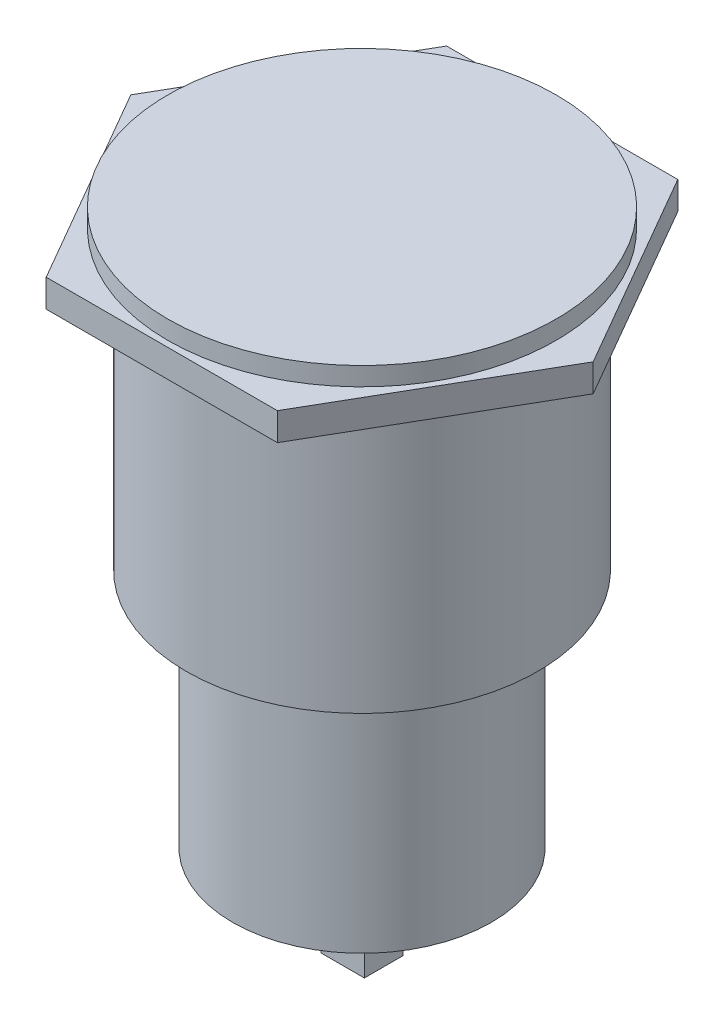
SolidWorks part; units mm, degrees
ref_plane "Front Plane" through (0, 0, 0) normal (0, 0, 1) x (1, 0, 0)
ref_plane "Top Plane" through (0, 0, 0) normal (0, 1, 0) x (1, 0, 0)
ref_plane "Right Plane" through (0, 0, 0) normal (1, 0, 0) x (0, 0, -1)
sketch "Sketch1" plane through (0, 0, 0) normal (0, 1, 0) x (1, 0, 0)
  circle A0 centre (0, 0) radius 9.5
  dimension "D1" = 19
extrude "Boss-Extrude1" add sketch "Sketch1" against normal blind 14.5
sketch "Sketch2" plane through (0, -14.5, 0) normal (0, -1, 0) x (1, 0, 0)
  circle A0 centre (0, 0) radius 7
  dimension "D1" = 14
extrude "Boss-Extrude2" add sketch "Sketch2" along normal blind 13
sketch "Sketch3" plane through (0, 0, 0) normal (0, 1, 0) x (1, 0, 0)
  line L1 (12.5, 0) -> (6.25, 10.8253)
  line L2 (6.25, 10.8253) -> (-6.25, 10.8253)
  line L3 (-6.25, 10.8253) -> (-12.5, 0)
  line L4 (-12.5, 0) -> (-6.25, -10.8253)
  line L5 (-6.25, -10.8253) -> (6.25, -10.8253)
  line L6 (6.25, -10.8253) -> (12.5, 0)
  circle A0 centre (0, 0) radius 10.8253 construction
  point P1 (0, 0)
  dimension "D1" = 25
extrude "Boss-Extrude3" add sketch "Sketch3" along normal blind 1.5
sketch "Sketch4" plane through (0, 1.5, 0) normal (0, 1, 0) x (1, 0, 0)
  circle A0 centre (0, 0) radius 10.5
  dimension "D1" = 21
extrude "Boss-Extrude4" add sketch "Sketch4" along normal blind 1
sketch "Sketch5" plane through (0, -27.5, 0) normal (0, -1, 0) x (1, 0, 0)
  line L1 (1.1683, -1.0405) -> (-1.1683, -1.0405)
  line L2 (1.1683, -1.0405) -> (1.1683, 1.0405)
  line L3 (1.1683, 1.0405) -> (-1.1683, 1.0405)
  line L4 (-1.1683, -1.0405) -> (-1.1683, 1.0405)
  line L5 (1.1683, -1.0405) -> (-1.1683, 1.0405) construction
  line L6 (1.1683, 1.0405) -> (-1.1683, -1.0405) construction
  point P0 (0, 0)
extrude "Boss-Extrude5" add sketch "Sketch5" along normal blind 5
